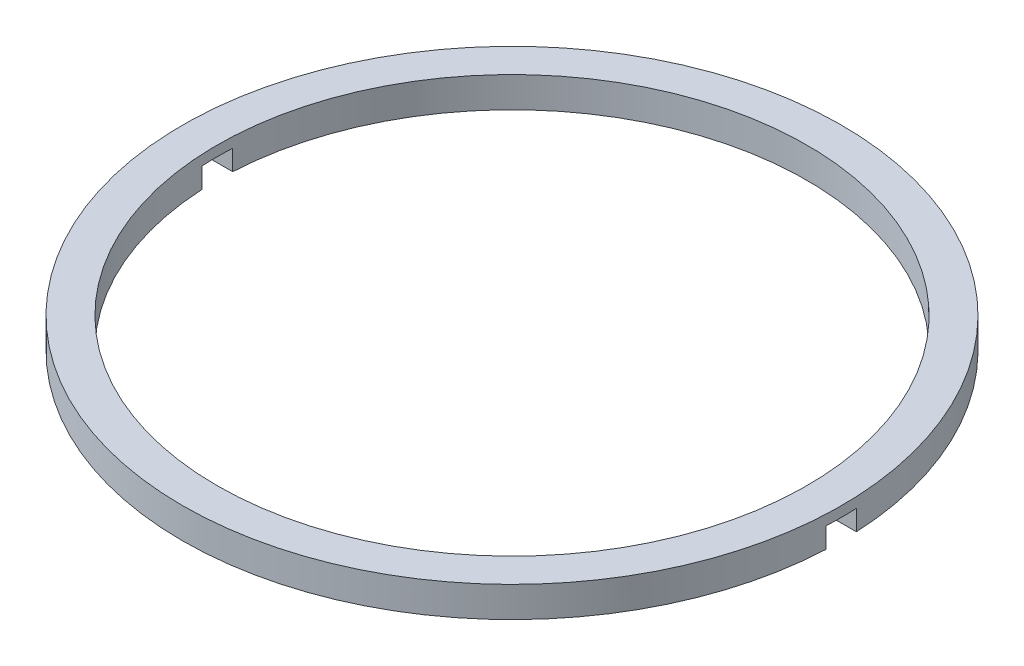
SolidWorks part; units mm, degrees
ref_plane "Спереди" through (0, 0, 0) normal (0, 0, 1) x (1, 0, 0)
ref_plane "Сверху" through (0, 0, 0) normal (0, 1, 0) x (1, 0, 0)
ref_plane "Справа" through (0, 0, 0) normal (1, 0, 0) x (0, 0, -1)
sketch "Эскиз2" plane through (0, 0, 0) normal (0, 1, 0) x (1, 0, 0)
  circle A0 centre (0, 0) radius 3.24
extrude "Бобышка-Вытянуть2" add sketch "Эскиз2" along normal blind 0.3
sketch "Эскиз3" plane through (0, 0, 0) normal (0, -1, 0) x (1, 0, 0)
  line L13 (3.5762, -0.15) -> (-3.5762, -0.15)
  line L21 (3.5762, -0.15) -> (3.5762, 0.15)
  line L22 (3.5762, 0.15) -> (-3.5762, 0.15)
  line L23 (-3.5762, -0.15) -> (-3.5762, 0.15)
  line L24 (3, 0.15) -> (3, -0.15)
  circle A0 centre (0, 0) radius 2.9
extrude "Вырез-Вытянуть1" cut sketch "Эскиз3" against normal blind 0.6 contours L22 A0 | L13 A0 L22 | L13 A0
sketch "Эскиз4" plane through (0, 0, 0) normal (0, -1, 0) x (1, 0, 0)
  line L1 (-3.7751, 0.15) -> (3.7751, 0.15)
  line L2 (-3.7751, 0.15) -> (-3.7751, -0.15)
  line L3 (-3.7751, -0.15) -> (3.7751, -0.15)
  line L4 (3.7751, 0.15) -> (3.7751, -0.15)
extrude "Вырез-Вытянуть2" cut sketch "Эскиз4" against normal blind 0.2
